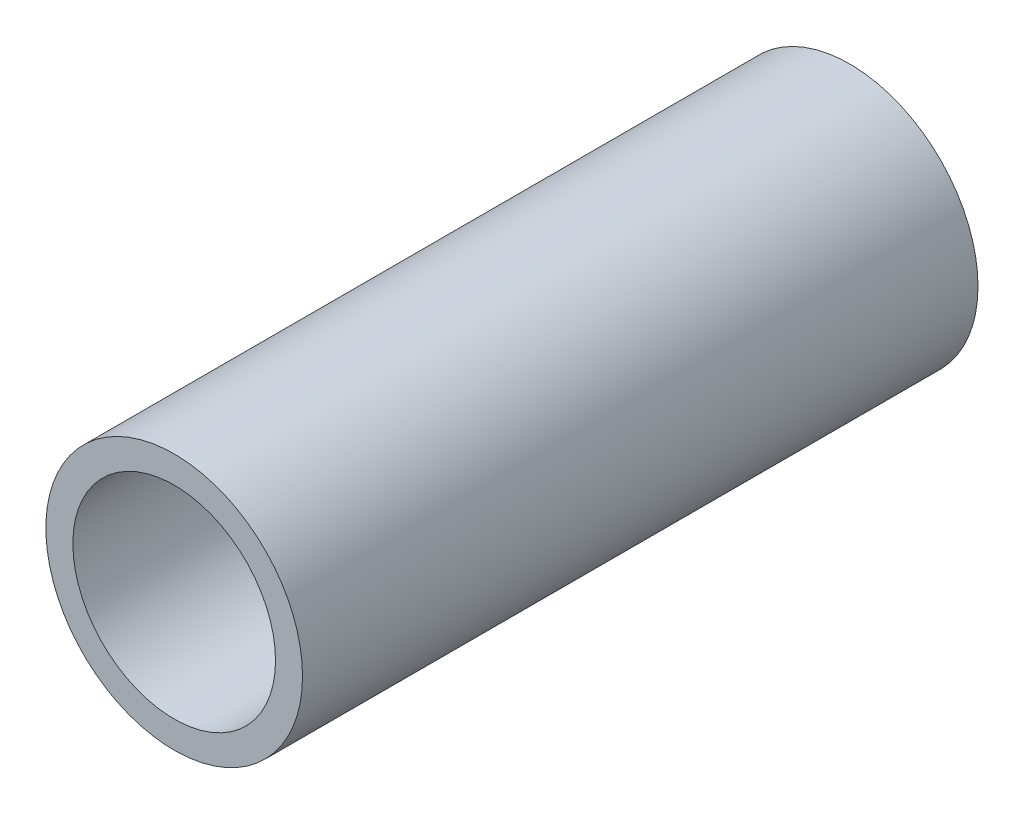
SolidWorks part; units mm, degrees
ref_plane "Front Plane" through (0, 0, 0) normal (0, 0, 1) x (1, 0, 0)
ref_plane "Top Plane" through (0, 0, 0) normal (0, 1, 0) x (1, 0, 0)
ref_plane "Right Plane" through (0, 0, 0) normal (1, 0, 0) x (0, 0, -1)
sketch "Sketch1" plane through (0, 0, 0) normal (0, 0, 1) x (1, 0, 0)
  circle A0 centre (50, 0) radius 7.5
  dimension "D1" = 15
extrude "Extrude-Thin1" add sketch "Sketch1" along normal blind 50 thin
